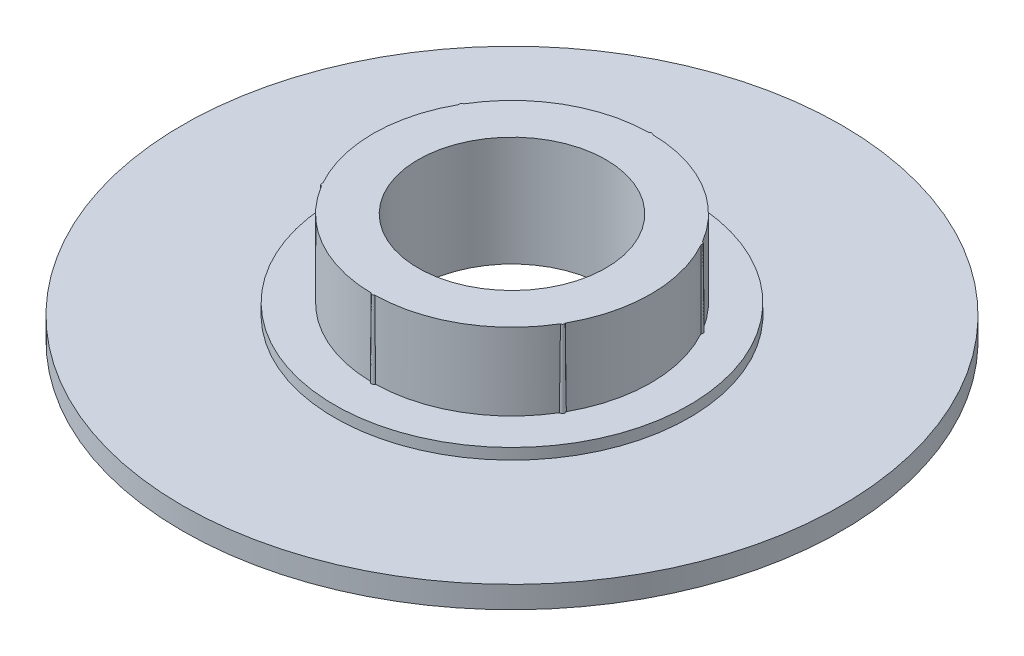
SolidWorks part; units mm, degrees
ref_plane "Front Plane" through (0, 0, 0) normal (0, 0, 1) x (1, 0, 0)
ref_plane "Top Plane" through (0, 0, 0) normal (0, 1, 0) x (1, 0, 0)
ref_plane "Right Plane" through (0, 0, 0) normal (1, 0, 0) x (0, 0, -1)
sketch "Sketch2" plane through (0, 0, 0) normal (0, 0, 1) x (1, 0, 0)
  line L0 (-8.55, 0) -> (-30, 0)
  line L1 (-30, 0) -> (-30, 2)
  line L2 (-30, 2) -> (-16.15, 2)
  line L3 (-16.15, 2) -> (-16.15, 3)
  line L4 (-16.15, 3) -> (-12.65, 3)
  line L5 (-12.65, 3) -> (-12.65, 10)
  line L6 (-12.65, 10) -> (-8.55, 10)
  line L7 (-8.55, 10) -> (-8.55, 0)
  line L8 (0, 0) -> (0, 14.7926) construction
  dimension "D1" = 30
  dimension "D2" = 2
  dimension "D3" = 1
  dimension "D4" = 3.5
  dimension "D5" = 8.55
  dimension "D6" = 12.65
  dimension "D7" = 10
revolve "Revolve1" add sketch "Sketch2" angle 360 about L8
sketch "Sketch3" plane through (0, 3, 0) normal (0, 1, 0) x (1, 0, 0)
  circle A0 centre (0, 0) radius 12.55 construction
  circle A1 centre (0, 0) radius 12.65 construction
  circle A2 centre (0, 12.55) radius 0.25
  circle A3 centre (10.8686, 6.275) radius 0.25
  circle A4 centre (10.8686, -6.275) radius 0.25
  circle A5 centre (0, -12.55) radius 0.25
  circle A6 centre (-10.8686, -6.275) radius 0.25
  circle A7 centre (-10.8686, 6.275) radius 0.25
  point P20 (0, 0)
  dimension "D1" = 0.1
  dimension "D2" = 0.5
  dimension "D3" = 6
extrude "Boss-Extrude1" add sketch "Sketch3" along normal up to surface (7 mm away) draft 0.5
